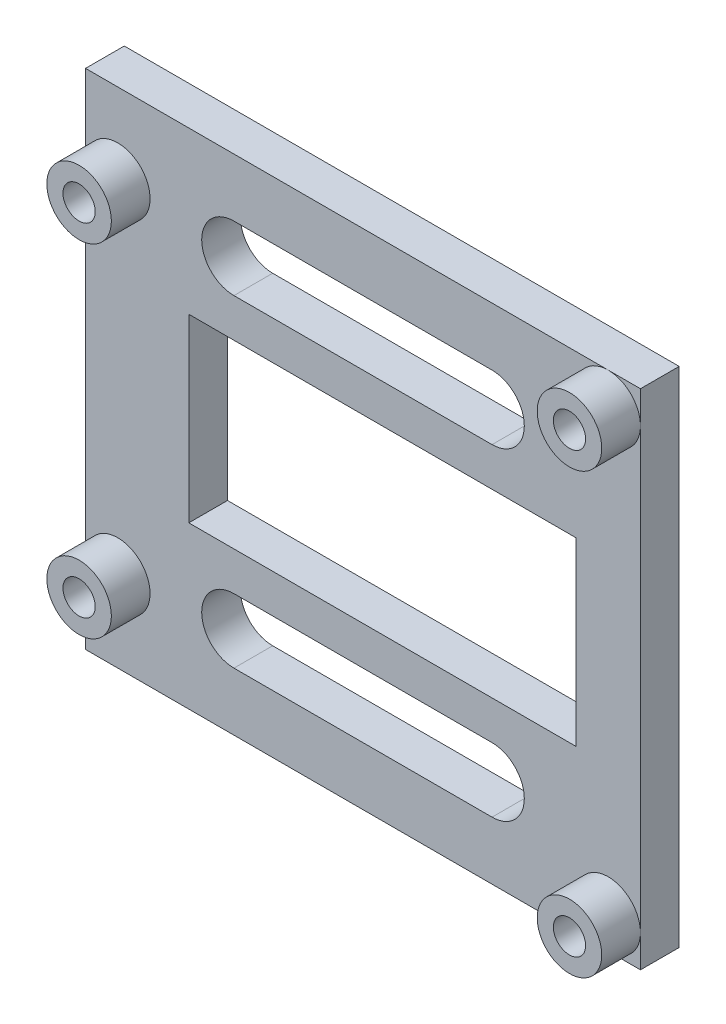
SolidWorks part; units mm, degrees
ref_plane "Piano frontale" through (0, 0, 0) normal (0, 0, 1) x (1, 0, 0)
ref_plane "Piano superiore" through (0, 0, 0) normal (0, 1, 0) x (1, 0, 0)
ref_plane "Piano destro" through (0, 0, 0) normal (1, 0, 0) x (0, 0, -1)
sketch "Schizzo1" plane through (0, 0, 0) normal (0, 0, 1) x (1, 0, 0)
  line L0 (-21.5, -19.5) -> (21.5, 19.5) construction
  line L1 (-21.5, 19.5) -> (21.5, 19.5)
  line L2 (-21.5, 19.5) -> (-21.5, -19.5)
  line L3 (-21.5, -19.5) -> (21.5, -19.5)
  line L4 (21.5, 19.5) -> (21.5, -19.5)
  dimension "D2" = 43
  dimension "D3" = 39
extrude "Estrusione-Estrusione1" add sketch "Schizzo1" along normal blind 3
sketch "Schizzo2" plane through (0, 0, 3) normal (0, 0, 1) x (1, 0, 0)
  line L0 (21.5, 19.5) -> (-21.5, 19.5) construction
  line L1 (21.5, -19.5) -> (21.5, 19.5) construction
  line L2 (19, 17) -> (19, -17) construction
  line L3 (19, 0) -> (-27.343, 0) construction
  circle A0 centre (19, 17) radius 2.5
  circle A1 centre (-19, 13.25) radius 2.5
  circle A2 centre (19, -17) radius 2.5
  circle A3 centre (-19, -13.25) radius 2.5
  dimension "D1" = 5
  dimension "D2" = 5
  dimension "D3" = 5
  dimension "D4" = 5
  dimension "D5" = 2.5
  dimension "D6" = 2.5
  dimension "D7" = 2.5
  dimension "D8" = 34
  dimension "D9" = 38
  dimension "D10" = 38
  dimension "D11" = 13.25
  dimension "D12" = 13.25
extrude "Estrusione-Estrusione2" add sketch "Schizzo2" along normal blind 3
sketch "Schizzo3" plane through (0, 0, 6) normal (0, 0, 1) x (1, 0, 0)
  circle A0 centre (-19, 13.25) radius 1.25
  circle A1 centre (19, 17) radius 1.25
  circle A2 centre (19, -17) radius 1.25
  circle A3 centre (-19, -13.25) radius 1.25
  dimension "D1" = 2.5
  dimension "D2" = 2.5
  dimension "D3" = 2.5
  dimension "D4" = 2.5
extrude "Taglio-Estrusione1" cut sketch "Schizzo3" against normal through all
sketch "Schizzo4" plane through (0, 0, 3) normal (0, 0, 1) x (1, 0, 0)
  line L0 (-21.5, 12.5) -> (21.5, 12.5) construction
  line L1 (-21.5, 19.5) -> (-21.5, 13.25) construction
  line L2 (19, 19.5) -> (-21.5, 19.5) construction
  line L3 (-10, 12.5) -> (10, 12.5) construction
  line L4 (-10, 15) -> (10, 15)
  line L5 (-10, 10) -> (10, 10)
  line L6 (21.5, -17) -> (21.5, 17) construction
  line L8 (-13.5, 7) -> (16.5, 7)
  line L9 (-13.5, 7) -> (-13.5, -7)
  line L10 (-13.5, -7) -> (16.5, -7)
  line L11 (16.5, 7) -> (16.5, -7)
  line L12 (-21.5, 13.25) -> (-21.5, -13.25) construction
  line L13 (-21.5, 0) -> (21.5, 0) construction
  line L14 (-10, -12.5) -> (10, -12.5) construction
  line L15 (-10, -15) -> (10, -15)
  line L16 (-10, -10) -> (10, -10)
  arc A0 (-10, 15) -> (-10, 10) centre (-10, 12.5) ccw
  arc A1 (10, 10) -> (10, 15) centre (10, 12.5) ccw
  arc A2 (-10, -15) -> (-10, -10) centre (-10, -12.5) cw
  arc A3 (10, -10) -> (10, -15) centre (10, -12.5) cw
  point P8 (0, 12.5)
  point P27 (0, -12.5)
  dimension "D1" = 7
  dimension "D2" = 5
  dimension "D3" = 20
  dimension "D4" = 3
  dimension "D5" = 3
  dimension "D6" = 8
  dimension "D7" = 5
extrude "Taglio-Estrusione2" cut sketch "Schizzo4" against normal through all
